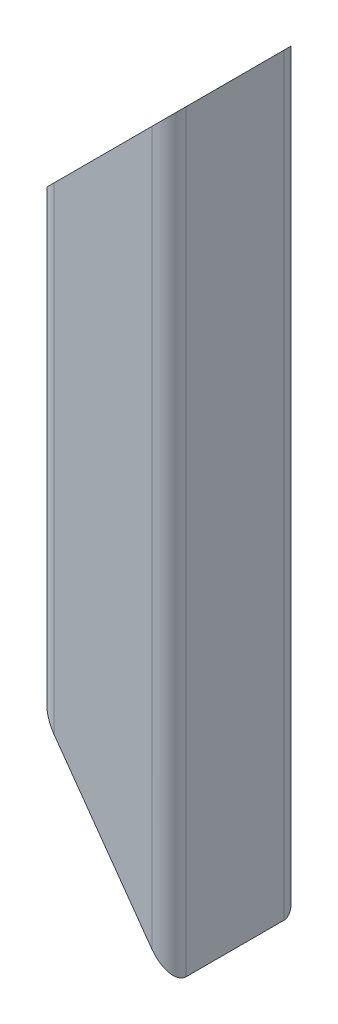
SolidWorks part; units mm, degrees
material "6061 Alloy"
ref_plane "Front Plane" through (0, 0, 0) normal (0, 0, 1) x (1, 0, 0)
ref_plane "Top Plane" through (0, 0, 0) normal (0, 1, 0) x (1, 0, 0)
ref_plane "Right Plane" through (0, 0, 0) normal (1, 0, 0) x (0, 0, -1)
sketch "Sketch1" plane through (0, 0, 0) normal (0, 1, 0) x (1, 0, 0)
  line L0 (-9.398, 0) -> (9.398, 0)
  line L1 (-12.7, 3.302) -> (-12.7, 22.098)
  line L2 (-9.398, 25.4) -> (9.398, 25.4)
  line L3 (12.7, 3.302) -> (12.7, 22.098)
  line L4 (-6.477, 3.175) -> (6.477, 3.175)
  line L5 (-9.525, 6.223) -> (-9.525, 19.177)
  line L6 (-6.477, 22.225) -> (6.477, 22.225)
  line L7 (9.525, 6.223) -> (9.525, 19.177)
  arc A0 (6.477, 22.225) -> (9.525, 19.177) centre (6.477, 19.177) cw
  arc A1 (6.477, 3.175) -> (9.525, 6.223) centre (6.477, 6.223) ccw
  arc A2 (-6.477, 3.175) -> (-9.525, 6.223) centre (-6.477, 6.223) cw
  arc A3 (-9.525, 19.177) -> (-6.477, 22.225) centre (-6.477, 19.177) cw
  arc A4 (9.398, 0) -> (12.7, 3.302) centre (9.398, 3.302) ccw
  arc A5 (-9.398, 0) -> (-12.7, 3.302) centre (-9.398, 3.302) cw
  arc A6 (-12.7, 22.098) -> (-9.398, 25.4) centre (-9.398, 22.098) cw
  arc A7 (9.398, 25.4) -> (12.7, 22.098) centre (9.398, 22.098) cw
  point P8 (0, 22.225)
  point P9 (0, 25.4)
  point P10 (-12.7, 12.7)
  point P11 (-9.525, 12.7)
  point P28 (0, 0)
  dimension "D2" = 3.048
  dimension "D3" = 3.302
  dimension "D1" = 3.175
  dimension "D4" = 25.4
extrude "Boss-Extrude1" add sketch "Sketch1" along normal blind 144.78
sketch "Sketch2" plane through (0, 0, 0) normal (0, 0, 1) x (1, 0, 0)
  line L0 (12.7, 144.78) -> (-12.7, 119.38)
  line L1 (-12.7, 144.78) -> (-12.7, 0) construction
  line L2 (-12.7, 119.38) -> (-12.7, 144.78)
  line L3 (-12.7, 144.78) -> (12.7, 144.78)
  line L4 (12.7, 0) -> (-12.7, 35.56)
  line L5 (-12.7, 35.56) -> (-12.7, 0)
  line L6 (-12.7, 0) -> (12.7, 0)
  dimension "D1" = 45
  dimension "D2" = 35.56
extrude "Cut-Extrude1" cut sketch "Sketch2" against normal through all
